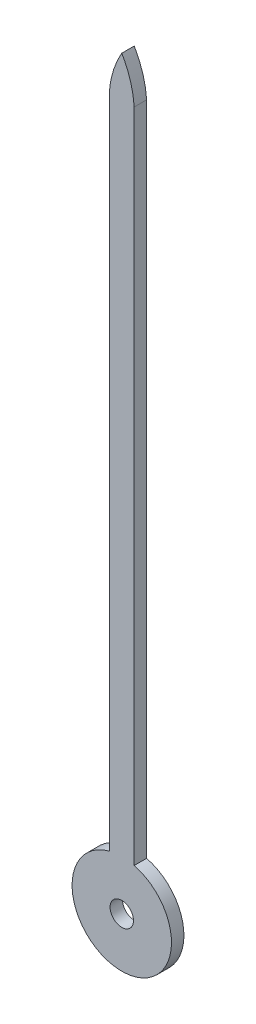
SolidWorks part; units mm, degrees
ref_plane "Front Plane" through (0, 0, 0) normal (0, 0, 1) x (1, 0, 0)
ref_plane "Top Plane" through (0, 0, 0) normal (0, 1, 0) x (1, 0, 0)
ref_plane "Right Plane" through (0, 0, 0) normal (1, 0, 0) x (0, 0, -1)
sketch "Sketch2" plane through (0, 0, 0) normal (0, 0, 1) x (1, 0, 0)
  line L0 (0, 0) -> (0, 90) construction
  line L1 (-1.5, 85.1251) -> (1.5, 85.1251) construction
  line L3 (-1.5, 85.1251) -> (-1.5, 5.8095)
  line L5 (1.5, 85.1251) -> (1.5, 5.8095)
  line L6 (0, 5.8095) -> (0, 90) construction
  line L7 (-1.5, 45.4673) -> (1.5, 45.4673) construction
  circle A0 centre (0, 0) radius 1.4125
  arc A1 (-1.5, 5.8095) -> (1.5, 5.8095) centre (0, 0) ccw
  spline S0 degree 2 poles (0, 90) (-1.3198, 87.7286) (-1.5, 85.1251) knots 0 0 0 1 1 1
  spline S1 degree 2 poles (0, 90) (1.3198, 87.7286) (1.5, 85.1251) knots 0 0 0 1 1 1
  point P165 (0, 45.4673)
  dimension "D1" = 12
  dimension "D2" = 3
  dimension "D3" = 85.1251
  dimension "D4" = 90
extrude "Boss-Extrude1" add sketch "Sketch2" along normal blind 1.5
